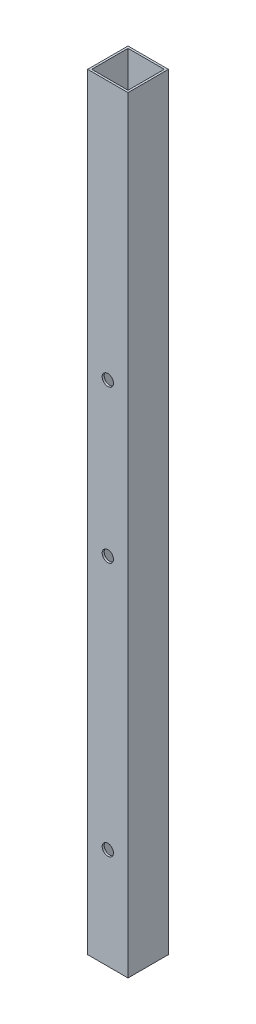
SolidWorks part; units mm, degrees
ref_plane "Front Plane" through (0, 0, 0) normal (0, 0, 1) x (1, 0, 0)
ref_plane "Top Plane" through (0, 0, 0) normal (0, 1, 0) x (1, 0, 0)
ref_plane "Right Plane" through (0, 0, 0) normal (1, 0, 0) x (0, 0, -1)
sketch "Sketch1" plane through (0, 0, 0) normal (0, 1, 0) x (1, 0, 0)
  line L0 (0, 0) -> (0, 25.4)
  line L1 (0, 25.4) -> (25.4, 25.4)
  line L2 (25.4, 25.4) -> (25.4, 0)
  line L3 (25.4, 0) -> (0, 0)
  line L6 (1.27, 12.3615) -> (1.27, 24.13)
  line L7 (1.27, 24.13) -> (12.7, 24.13)
  line L10 (12.7, 24.13) -> (24.13, 24.13)
  line L11 (24.13, 24.13) -> (24.13, 12.7)
  line L12 (24.13, 1.27) -> (24.13, 12.7)
  line L13 (24.13, 1.27) -> (12.7, 1.27)
  line L14 (1.27, 1.27) -> (12.7, 1.27)
  line L15 (1.27, 12.3615) -> (1.27, 1.27)
  dimension "D1" = 25.4
  dimension "D2" = 25.4
  dimension "D3" = 11.7685
  dimension "D4" = 11.0915
  dimension "D5" = 11.43
  dimension "D6" = 11.43
extrude "Boss-Extrude1" add sketch "Sketch1" along normal blind 482.6
sketch "Sketch3" plane through (0, 0, -25.4) normal (0, 0, -1) x (-1, 0, 0)
  circle A0 centre (-12.762, 449.168) radius 2.54
extrude "Cut-Extrude1" cut sketch "Sketch3" against normal blind 2.54
sketch "Sketch4" plane through (0, 0, -25.4) normal (0, 0, -1) x (-1, 0, 0)
  circle A1 centre (-12.7006, 321.2008) radius 2.54
extrude "Cut-Extrude2" cut sketch "Sketch4" against normal blind 2.54
sketch "Sketch5" plane through (0, 0, -25.4) normal (0, 0, -1) x (-1, 0, 0)
  circle A0 centre (-12.716, 18.4179) radius 2.54
extrude "Cut-Extrude3" cut sketch "Sketch5" against normal blind 2.54
sketch "Sketch6" plane through (0, 0, 0) normal (0, 0, 1) x (1, 0, 0)
  circle A0 centre (12.7, 63.552) radius 3.556
extrude "Cut-Extrude4" cut sketch "Sketch6" against normal blind 2.54
sketch "Sketch7" plane through (0, 0, 0) normal (0, 0, 1) x (1, 0, 0)
  circle A0 centre (12.7, 223.6) radius 3.556
  circle A1 centre (12.7, 319.6) radius 3.556
extrude "Cut-Extrude5" cut sketch "Sketch7" against normal blind 2.54
